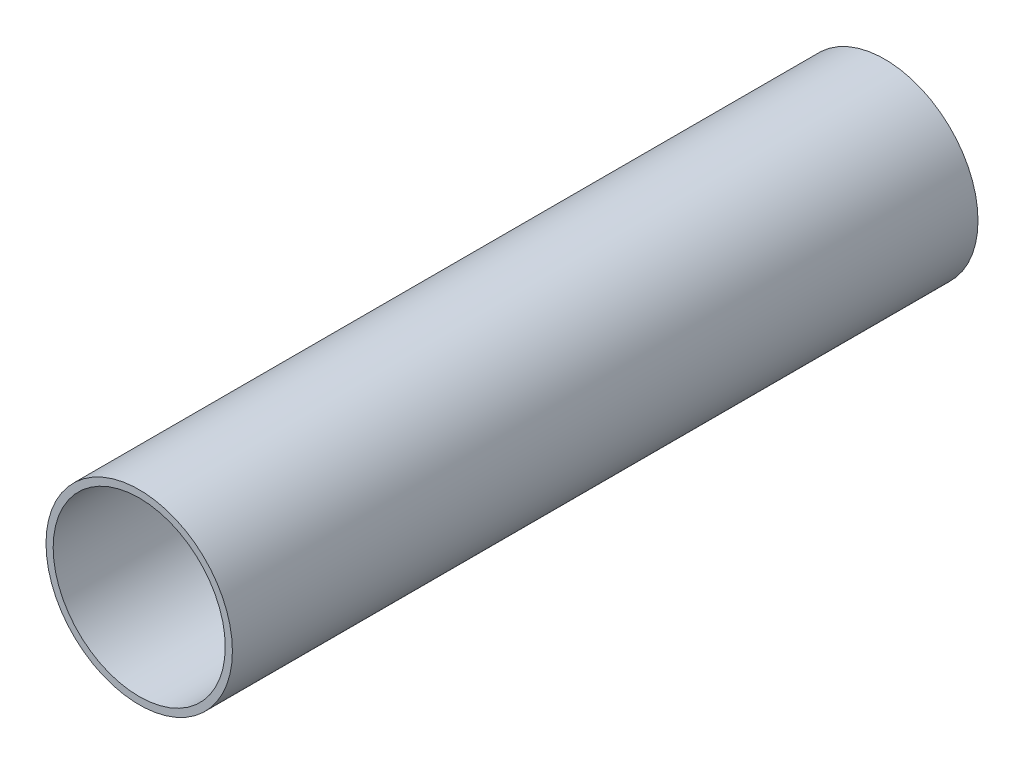
SolidWorks part; units mm, degrees
ref_plane "Front Plane" through (0, 0, 0) normal (0, 0, 1) x (1, 0, 0)
ref_plane "Top Plane" through (0, 0, 0) normal (0, 1, 0) x (1, 0, 0)
ref_plane "Right Plane" through (0, 0, 0) normal (1, 0, 0) x (0, 0, -1)
sketch "Sketch1" plane through (0, 0, 0) normal (0, 0, 1) x (1, 0, 0)
  circle A0 centre (0, 0) radius 11.54
  circle A1 centre (0, 0) radius 12.5
  dimension "D1" = 23.08
  dimension "D2" = 25
extrude "Boss-Extrude2" add sketch "Sketch1" along normal blind 100
